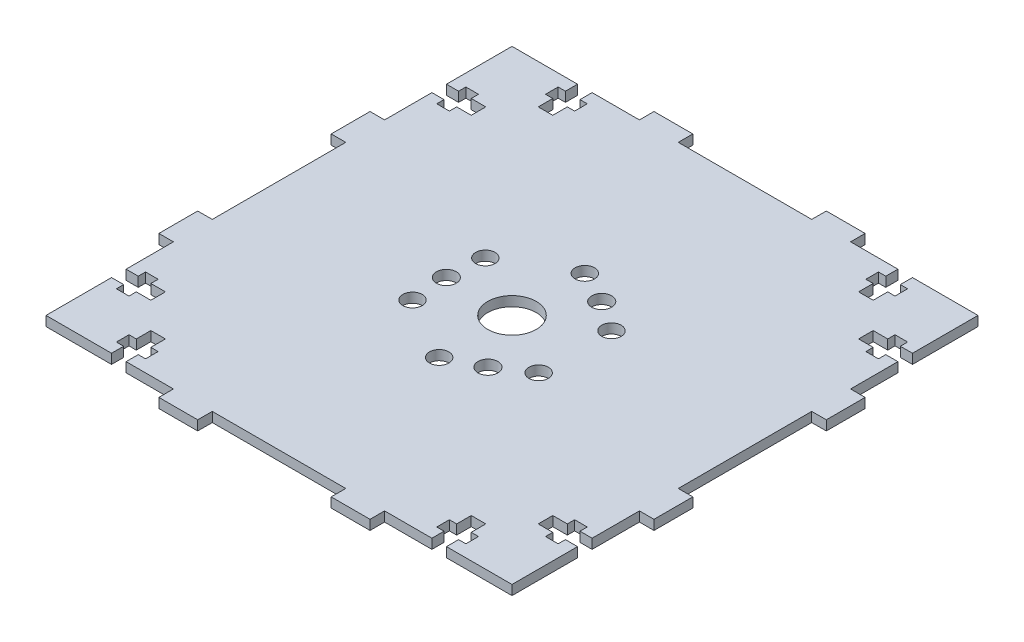
SolidWorks part; units mm, degrees
ref_plane "前视基准面" through (0, 0, 0) normal (0, 0, 1) x (1, 0, 0)
ref_plane "上视基准面" through (0, 0, 0) normal (0, 1, 0) x (1, 0, 0)
ref_plane "右视基准面" through (0, 0, 0) normal (1, 0, 0) x (0, 0, -1)
sketch "草图1" plane through (0, 0, 0) normal (0, 1, 0) x (1, 0, 0)
  line L19 (-31.5, -48) -> (-21.75, -48)
  line L62 (-21.75, -51) -> (-13.75, -51)
  line L123 (-13.75, -48) -> (13.75, -48)
  line L134 (-30, -45.5) -> (-30, -42.9)
  line L211 (35.5, -48) -> (47.5, -48)
  line L214 (21.75, -48) -> (31.5, -48)
  line L216 (-34.5, -45.5) -> (-34.5, -48)
  line L217 (-30, -42.9) -> (-31.5, -42.9)
  line L297 (-31.5, -42.9) -> (-31.5, -39.9)
  line L312 (-31.5, -39.9) -> (-34.5, -39.9)
  line L315 (34.5, -45.5) -> (36, -45.5)
  line L342 (31.5, -45.5) -> (30, -45.5)
  line L354 (-34.5, -42.9) -> (-34.5, -39.9)
  line L358 (31.5, -48) -> (31.5, -45.5)
  line L359 (36, -45.5) -> (36, -42.9)
  line L360 (36, -42.9) -> (34.5, -42.9)
  line L361 (34.5, -42.9) -> (34.5, -39.9)
  line L362 (31.5, -39.9) -> (34.5, -39.9)
  line L363 (31.5, -42.9) -> (31.5, -39.9)
  line L364 (30, -42.9) -> (31.5, -42.9)
  line L365 (30, -45.5) -> (30, -42.9)
  line L382 (34.5, -45.5) -> (34.5, -48)
  line L389 (-36, -42.9) -> (-34.5, -42.9)
  line L390 (-36, -45.5) -> (-36, -42.9)
  line L391 (-31.5, -48) -> (-31.5, -45.5)
  line L392 (-31.5, -45.5) -> (-30, -45.5)
  line L393 (-34.5, -45.5) -> (-36, -45.5)
  line L395 (-34.5, -48) -> (-47, -48)
  line L426 (-21.75, -48) -> (-21.75, -51)
  line L489 (21.75, -51) -> (13.75, -51)
  line L492 (-13.75, -51) -> (-13.75, -48)
  line L493 (13.75, -48) -> (13.75, -51)
  line L494 (21.75, -51) -> (21.75, -48)
  line L496 (-48, -21.75) -> (-48, -31.5)
  line L497 (-45.5, -34.5) -> (-45.5, -36)
  line L498 (-45.5, -31.5) -> (-45.5, -30)
  line L499 (-48, -31.5) -> (-45.5, -31.5)
  line L500 (-45.5, -36) -> (-42.9, -36)
  line L501 (-42.9, -36) -> (-42.9, -34.5)
  line L505 (-42.9, -30) -> (-42.9, -31.5)
  line L506 (-45.5, -30) -> (-42.9, -30)
  line L507 (-45.5, -34.5) -> (-48, -34.5)
  line L508 (-48, 31.5) -> (-48, 21.75)
  line L509 (-45.5, 30) -> (-42.9, 30)
  line L510 (-45.5, 34.5) -> (-48, 34.5)
  line L511 (-42.9, 30) -> (-42.9, 31.5)
  line L512 (-42.9, 31.5) -> (-39.9, 31.5)
  line L513 (-39.9, 31.5) -> (-39.9, 34.5)
  line L514 (-42.9, 34.5) -> (-39.9, 34.5)
  line L515 (-42.9, 36) -> (-42.9, 34.5)
  line L516 (-45.5, 36) -> (-42.9, 36)
  line L517 (-48, 31.5) -> (-45.5, 31.5)
  line L518 (-45.5, 31.5) -> (-45.5, 30)
  line L519 (-45.5, 34.5) -> (-45.5, 36)
  line L520 (-48, 34.5) -> (-48, 47)
  line L521 (-48, 21.75) -> (-51, 21.75)
  line L522 (-51, 13.75) -> (-48, 13.75)
  line L524 (-51, -21.75) -> (-51, -13.75)
  line L525 (-48, -13.75) -> (-51, -13.75)
  line L526 (-51, -21.75) -> (-48, -21.75)
  line L527 (-51, 21.75) -> (-51, 13.75)
  line L529 (-21.75, 48) -> (-31.5, 48)
  line L530 (-34.5, 45.5) -> (-36, 45.5)
  line L531 (-31.5, 45.5) -> (-30, 45.5)
  line L532 (-31.5, 48) -> (-31.5, 45.5)
  line L533 (-36, 45.5) -> (-36, 42.9)
  line L534 (-36, 42.9) -> (-34.5, 42.9)
  line L535 (-34.5, 42.9) -> (-34.5, 39.9)
  line L536 (-31.5, 39.9) -> (-34.5, 39.9)
  line L537 (-31.5, 42.9) -> (-31.5, 39.9)
  line L538 (-30, 42.9) -> (-31.5, 42.9)
  line L539 (-30, 45.5) -> (-30, 42.9)
  line L540 (-34.5, 45.5) -> (-34.5, 48)
  line L541 (31.5, 48) -> (21.75, 48)
  line L542 (30, 45.5) -> (30, 42.9)
  line L543 (34.5, 45.5) -> (34.5, 48)
  line L544 (30, 42.9) -> (31.5, 42.9)
  line L545 (31.5, 42.9) -> (31.5, 39.9)
  line L546 (31.5, 39.9) -> (34.5, 39.9)
  line L547 (34.5, 42.9) -> (34.5, 39.9)
  line L548 (36, 42.9) -> (34.5, 42.9)
  line L549 (36, 45.5) -> (36, 42.9)
  line L550 (31.5, 48) -> (31.5, 45.5)
  line L551 (31.5, 45.5) -> (30, 45.5)
  line L552 (34.5, 45.5) -> (36, 45.5)
  line L554 (21.75, 48) -> (21.75, 51)
  line L555 (13.75, 51) -> (13.75, 48)
  line L556 (13.75, 48) -> (-13.75, 48)
  line L557 (-21.75, 51) -> (-13.75, 51)
  line L558 (-13.75, 48) -> (-13.75, 51)
  line L559 (-21.75, 51) -> (-21.75, 48)
  line L560 (21.75, 51) -> (13.75, 51)
  line L561 (48, 34.5) -> (48, 46.5)
  line L562 (48, 21.75) -> (48, 31.5)
  line L563 (45.5, 34.5) -> (45.5, 36)
  line L564 (45.5, 31.5) -> (45.5, 30)
  line L565 (48, 31.5) -> (45.5, 31.5)
  line L566 (45.5, 36) -> (42.9, 36)
  line L567 (42.9, 36) -> (42.9, 34.5)
  line L568 (42.9, 34.5) -> (39.9, 34.5)
  line L569 (39.9, 31.5) -> (39.9, 34.5)
  line L570 (42.9, 31.5) -> (39.9, 31.5)
  line L571 (42.9, 30) -> (42.9, 31.5)
  line L572 (45.5, 30) -> (42.9, 30)
  line L573 (45.5, 34.5) -> (48, 34.5)
  line L574 (48, -31.5) -> (48, -21.75)
  line L575 (45.5, -30) -> (42.9, -30)
  line L576 (45.5, -34.5) -> (48, -34.5)
  line L577 (42.9, -30) -> (42.9, -31.5)
  line L578 (42.9, -31.5) -> (39.9, -31.5)
  line L579 (39.9, -31.5) -> (39.9, -34.5)
  line L580 (42.9, -34.5) -> (39.9, -34.5)
  line L581 (42.9, -36) -> (42.9, -34.5)
  line L582 (45.5, -36) -> (42.9, -36)
  line L583 (48, -31.5) -> (45.5, -31.5)
  line L584 (45.5, -31.5) -> (45.5, -30)
  line L585 (45.5, -34.5) -> (45.5, -36)
  line L586 (48, -35.5) -> (48, -48)
  line L587 (48, -21.75) -> (51, -21.75)
  line L588 (51, -13.75) -> (48, -13.75)
  line L589 (48, -13.75) -> (48, 13.75)
  line L590 (51, 21.75) -> (51, 13.75)
  line L591 (48, 13.75) -> (51, 13.75)
  line L592 (51, 21.75) -> (48, 21.75)
  line L593 (51, -21.75) -> (51, -13.75)
  line L596 (-48, -35.5) -> (-48, -34.5)
  line L598 (35.5, 48) -> (34.5, 48)
  line L600 (35.5, -48) -> (34.5, -48)
  line L601 (48, -35.5) -> (48, -34.5)
  line L602 (0, 0) -> (-13.53, 0) construction
  line L603 (-42.9, -31.5) -> (-39.9, -31.5)
  line L604 (-34.5, 48) -> (-42.9, 48)
  line L605 (-39.9, -31.5) -> (-39.9, -34.5)
  line L606 (-39.9, -34.5) -> (-42.9, -34.5)
  line L609 (-42.9, 48) -> (-48, 48)
  line L611 (-47, -48) -> (-48, -48)
  line L612 (47.5, -48) -> (48, -48)
  line L613 (35.5, 48) -> (48, 48)
  line L614 (48, 48) -> (48, 46.5)
  line L615 (-48, 13.75) -> (-48, -13.75)
  line L616 (-48, -35.5) -> (-48, -48)
  line L617 (-48, 47) -> (-48, 48)
  circle A38 centre (0, 0) radius 15 construction
  circle A39 centre (0, 0) radius 13.53 construction
  circle A40 centre (0, -15) radius 2
  circle A41 centre (-12.9904, -7.5) radius 2
  circle A42 centre (-12.9904, 7.5) radius 2
  circle A43 centre (0, 15) radius 2
  circle A48 centre (12.9904, 7.5) radius 2
  circle A49 centre (12.9904, -7.5) radius 2
  circle A50 centre (-13.53, 0) radius 2.05
  circle A51 centre (6.765, 11.7173) radius 2.05
  circle A52 centre (6.765, -11.7173) radius 2.05
  circle A53 centre (0, 0) radius 5
  point P21 (-33.5, -39.4)
  point P45 (-39.4, 33.5)
  point P74 (0, 0)
  point P97 (33.5, 39.4)
  point P129 (-32.5, 39.4)
  point P134 (32.5, -39.4)
  point P146 (39.4, -33.5)
  point P168 (39.4, 32.5)
  dimension "D2" = 3
  dimension "D1" = 6
extrude "凸台-拉伸1" add sketch "草图1" along normal blind 2
sketch "草图3" plane through (0, 0, 48) normal (0, 0, 1) x (1, 0, 0)
  line L0 (-34.5, 0) -> (-31.5, 2)
  circle A0 centre (-33, 1) radius 1.5
sketch "草图4" plane through (48, 0, 0) normal (1, 0, 0) x (0, 0, -1)
  line L0 (-31.5, 2) -> (-34.5, 0)
  circle A0 centre (-33, 1) radius 1.5
sketch "草图6" plane through (-48, 0, 0) normal (-1, 0, 0) x (0, 0, 1)
  line L0 (-34.5, 2) -> (-31.5, 0)
  circle A0 centre (-33, 1) radius 1.5
sketch "草图8" plane through (0, 0, -48) normal (0, 0, -1) x (-1, 0, 0)
  line L0 (-31.5, 0) -> (-34.5, 2)
  circle A0 centre (-33, 1) radius 1.5
